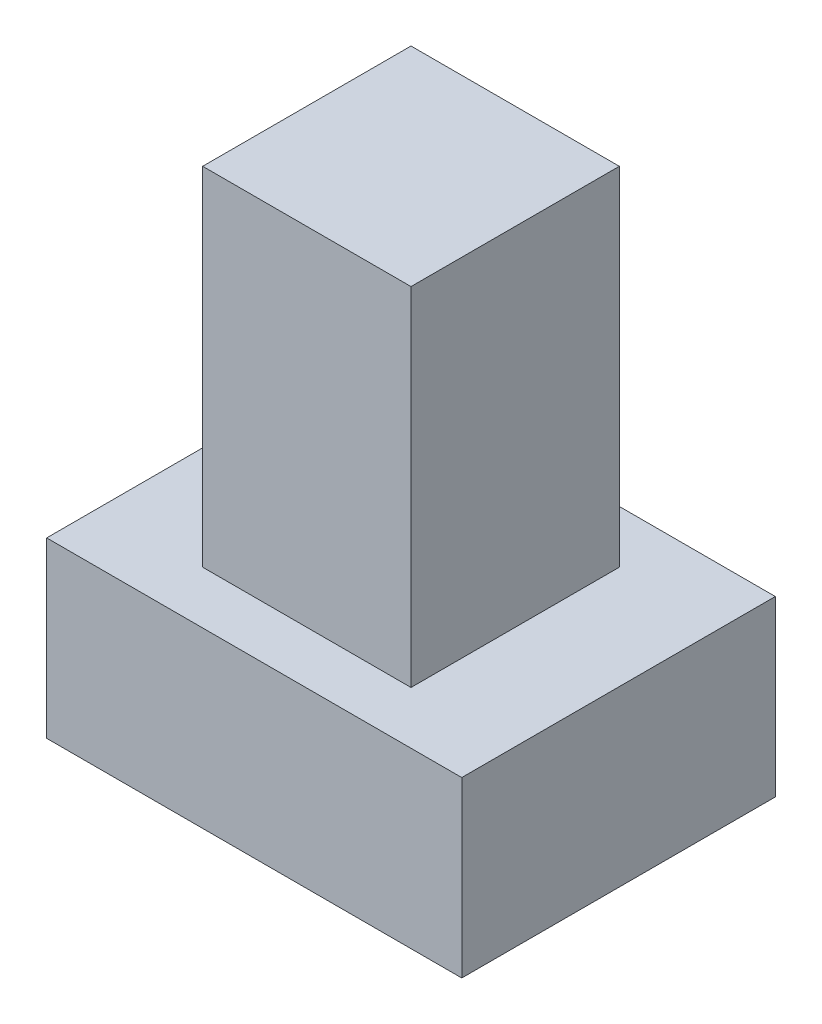
SolidWorks part; units mm, degrees
ref_plane "Front Plane" through (0, 0, 0) normal (0, 0, 1) x (1, 0, 0)
ref_plane "Top Plane" through (0, 0, 0) normal (0, 1, 0) x (1, 0, 0)
ref_plane "Right Plane" through (0, 0, 0) normal (1, 0, 0) x (0, 0, -1)
sketch "Sketch1" plane through (0, 0, 0) normal (0, 1, 0) x (1, 0, 0)
  line L1 (0, 0) -> (11.9544, 0)
  line L2 (0, 0) -> (0, 9.0308)
  line L3 (0, 9.0308) -> (11.9544, 9.0308)
  line L4 (11.9544, 0) -> (11.9544, 9.0308)
extrude "Boss-Extrude1" add sketch "Sketch1" along normal blind 5
sketch "Sketch7" plane through (0, 5, 0) normal (0, 1, 0) x (1, 0, 0)
  line L7 (2.9772, 7.5154) -> (8.9772, 7.5154)
  line L8 (2.9772, 7.5154) -> (2.9772, 1.5154)
  line L9 (2.9772, 1.5154) -> (8.9772, 1.5154)
  line L10 (8.9772, 7.5154) -> (8.9772, 1.5154)
  point P12 (5.9772, 4.5154)
extrude "Boss-Extrude2" add sketch "Sketch7" along normal blind 10
ref_plane "Plane1" through (11.9544, 5, 0) normal (1, 0, 0) x (0, 0, -1)
sketch "Sketch8" plane through (11.9544, 5, 0) normal (1, 0, 0) x (0, 0, -1)
